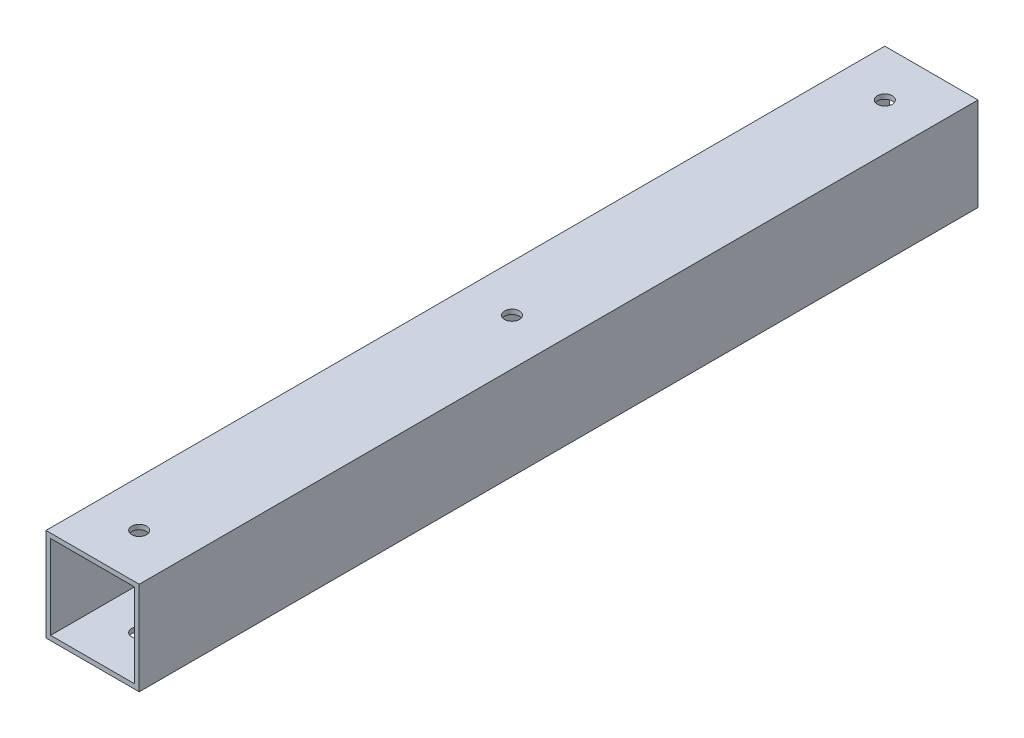
SolidWorks part; units mm, degrees
ref_plane "前视基准面" through (0, 0, 0) normal (0, 0, 1) x (1, 0, 0)
ref_plane "上视基准面" through (0, 0, 0) normal (0, 1, 0) x (1, 0, 0)
ref_plane "右视基准面" through (0, 0, 0) normal (1, 0, 0) x (0, 0, -1)
other "Configuration Table"
sketch "草图1" plane through (0, 0, 0) normal (0, 0, 1) x (1, 0, 0)
  line L1 (-9, 9) -> (9, 9)
  line L2 (-9, 9) -> (-9, -9)
  line L3 (-9, -9) -> (9, -9)
  line L4 (9, 9) -> (9, -9)
  line L5 (-9, 9) -> (9, -9) construction
  line L6 (-9, -9) -> (9, 9) construction
  line L7 (-10, 10) -> (10, 10)
  line L8 (-10, 10) -> (-10, -10)
  line L9 (-10, -10) -> (10, -10)
  line L10 (10, 10) -> (10, -10)
  line L11 (-10, 10) -> (10, -10) construction
  line L12 (-10, -10) -> (10, 10) construction
  point P0 (0, 0)
  point P6 (0, 0)
  dimension "D1" = 20
  dimension "D2" = 20
  dimension "D3" = 1
  dimension "D4" = 1
extrude "凸台-拉伸1" add sketch "草图1" along normal blind 180
sketch "草图2" plane through (0, 10, 0) normal (0, 1, 0) x (1, 0, 0)
  line L0 (-10, -90) -> (10, -90) construction
  line L1 (-10, -180) -> (-10, 0) construction
  line L2 (10, -180) -> (10, 0) construction
  line L3 (0, -180) -> (0, 0) construction
  line L4 (10, -180) -> (-10, -180) construction
  circle A0 centre (0, -90) radius 1.6
  circle A1 centre (0, -170) radius 1.6
  circle A2 centre (0, -10) radius 1.6
  dimension "D1" = 3.2
  dimension "D2" = 80
  dimension "D3" = 80
extrude "切除-拉伸1" cut sketch "草图2" against normal blind 50
